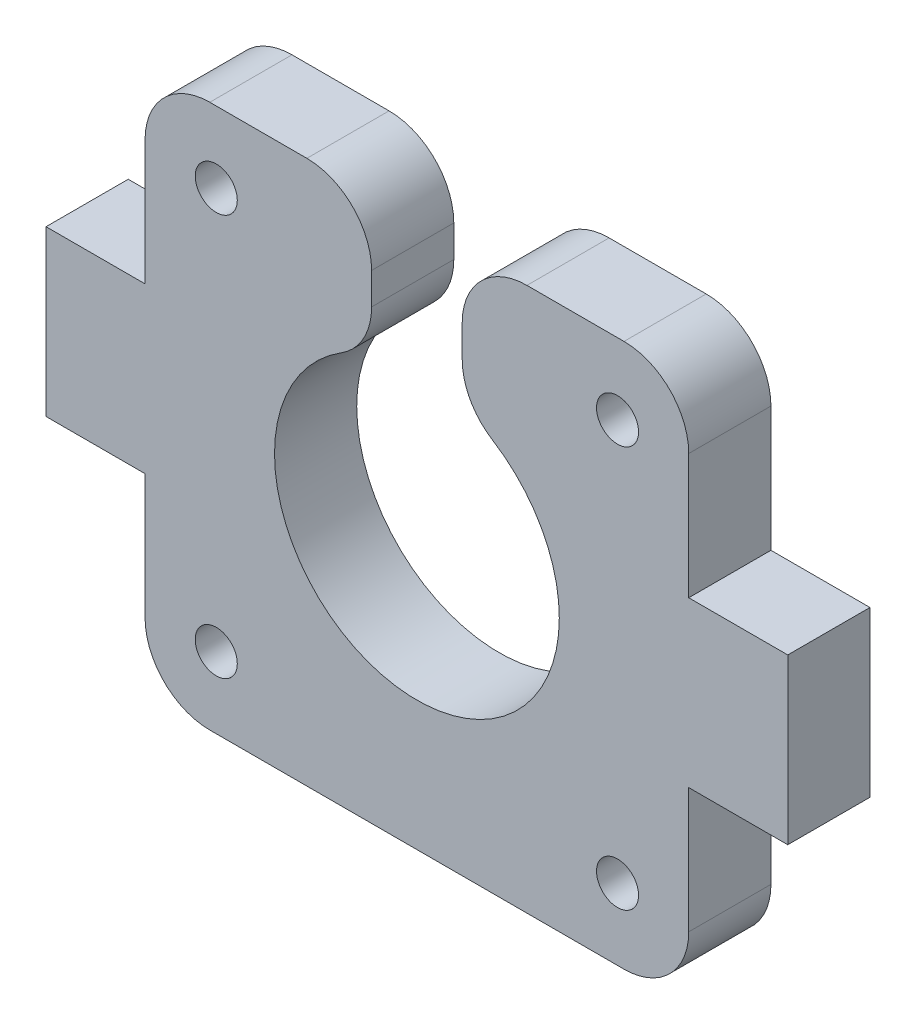
SolidWorks part; units mm, degrees
ref_plane "Front Plane" through (0, 0, 0) normal (0, 0, 1) x (1, 0, 0)
ref_plane "Top Plane" through (0, 0, 0) normal (0, 1, 0) x (1, 0, 0)
ref_plane "Right Plane" through (0, 0, 0) normal (1, 0, 0) x (0, 0, -1)
sketch "Sketch1" plane through (0, 0, 0) normal (0, 0, 1) x (1, 0, 0)
  line L1 (28.65, -21) -> (-28.65, -21)
  line L2 (28.65, -21) -> (28.65, 21)
  line L3 (28.65, 21) -> (-28.65, 21)
  line L4 (-28.65, -21) -> (-28.65, 21)
  line L5 (28.65, -21) -> (-28.65, 21) construction
  line L6 (28.65, 21) -> (-28.65, -21) construction
  point P0 (0, 0)
  dimension "D1" = 57.3
  dimension "D2" = 42
extrude "Boss-Extrude1" add sketch "Sketch1" along normal blind 6.35
hole_wizard "Tap Drill for M3x0.5 Tap1" positions "Sketch2" profile "Sketch3" hole size "M3x0.5" standard "ANSI Metric" end condition up to next
sketch "Sketch2" plane through (0, 0, 6.35) normal (0, 0, 1) x (1, 0, 0)
  line L0 (-15.5, 15.5) -> (15.5, 15.5) construction
  line L1 (15.5, 15.5) -> (15.5, -15.5) construction
  line L2 (15.5, -15.5) -> (-15.5, -15.5) construction
  line L3 (-15.5, -15.5) -> (-15.5, 15.5) construction
  line L4 (-15.5, 15.5) -> (15.5, -15.5) construction
  line L5 (15.5, -15.5) -> (-15.5, -15.5) construction
  line L6 (-15.5, -15.5) -> (15.5, 15.5) construction
  point P0 (15.5, 15.5)
  point P2 (15.5, -15.5)
  point P4 (-15.5, 15.5)
  point P6 (-15.5, -15.5)
  point P24 (0, 0)
  dimension "D1" = 31
sketch "Sketch3" plane through (15.5, 15.5, 6.35) normal (1, 0, 0) x (0, -1, 0)
  line L0 (0, 0) -> (0, 6.35)
  line L1 (0, 6.35) -> (1.625, 6.35)
  line L2 (1.625, 6.35) -> (1.625, 0)
  line L5 (1.625, 0) -> (0, 0)
  line L11 (0, -6.35) -> (0, 107.95) construction
  dimension "Thru Hole Dia." = 3.25
  dimension "Thru Hole Depth" = 6.35
sketch "Sketch4" plane through (0, 0, 6.35) normal (0, 0, 1) x (1, 0, 0)
  line L0 (28.65, 21) -> (-28.65, 21) construction
  line L1 (3.5, 10.4283) -> (-3.5, 10.4283)
  line L2 (3.5, 10.4283) -> (3.5, 21)
  line L3 (3.5, 21) -> (-3.5, 21)
  line L4 (-3.5, 10.4283) -> (-3.5, 21)
  line L5 (3.5, 10.4283) -> (-3.5, 21) construction
  line L6 (3.5, 21) -> (-3.5, 10.4283) construction
  circle A0 centre (0, 0) radius 11
  point P3 (0, 15.7142)
  line M8 (28.65, 21) -> (-28.65, 21)
  dimension "D1" = 22
  dimension "D2" = 7
extrude "Cut-Extrude1" cut sketch "Sketch4" against normal through all contours L1 A0 | A0 L2 L4 M8 | L1 A0
sketch "Sketch5" plane through (0, 0, 6.35) normal (0, 0, 1) x (1, 0, 0)
  line L0 (-28.65, 21) -> (-28.65, -21) construction
  line L1 (-21, 6.35) -> (-28.65, 6.35)
  line L2 (-21, 6.35) -> (-21, 21)
  line L3 (-21, 21) -> (-28.65, 21)
  line L4 (-28.65, 6.35) -> (-28.65, 21)
  line L5 (-21, 6.35) -> (-28.65, 21) construction
  line L6 (-21, 21) -> (-28.65, 6.35) construction
  line L9 (-28.65, -21) -> (28.65, -21) construction
  line L10 (-28.65, 21) -> (-28.65, -21) construction
  line L11 (-28.65, -6.35) -> (-21, -6.35)
  line L12 (-28.65, -6.35) -> (-28.65, -21)
  line L13 (-28.65, -21) -> (-21, -21)
  line L14 (-21, -6.35) -> (-21, -21)
  line L15 (-28.65, -6.35) -> (-21, -21) construction
  line L16 (-28.65, -21) -> (-21, -6.35) construction
  line L17 (-21, -6.35) -> (-21, 6.35) construction
  line L18 (-3.5, 21) -> (-28.65, 21) construction
  point P0 (-24.825, 13.675)
  point P9 (-21, 0)
  point P12 (-24.825, -13.675)
  dimension "D1" = 12.7
  dimension "D2" = 21
extrude "Cut-Extrude2" cut sketch "Sketch5" against normal through all
mirror "Mirror1" about plane through (0, 0, 0) normal (1, 0, 0) of "Cut-Extrude2"
fillet "Fillet1" radius 5 8 edges at (3.5, 21, 3.175) (-3.5, 21, 3.175) (-3.5, 10.4283, 3.175) (3.5, 10.4283, 3.175) (-21, -21, 3.175) (21, -21, 3.175) (21, 21, 3.175) (-21, 21, 3.175)
